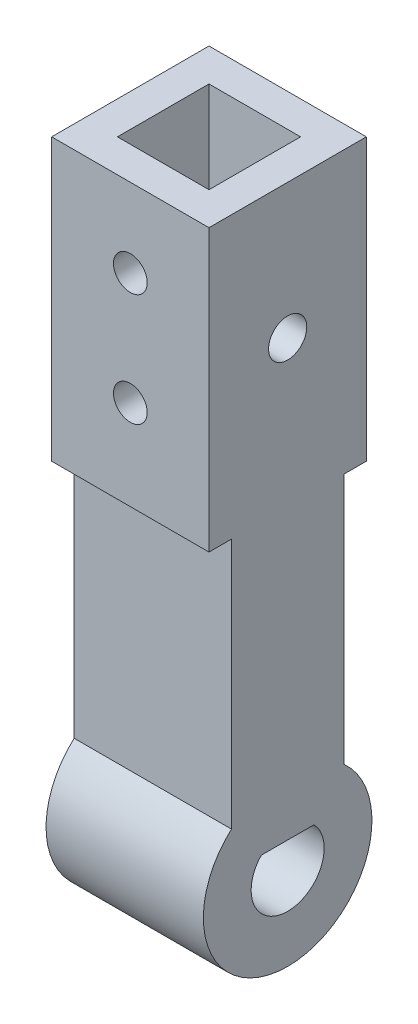
SolidWorks part; units mm, degrees
material "PLA"
ref_plane "Plan de face" through (0, 0, 0) normal (0, 0, 1) x (1, 0, 0)
ref_plane "Plan de dessus" through (0, 0, 0) normal (0, 1, 0) x (1, 0, 0)
ref_plane "Plan de droite" through (0, 0, 0) normal (1, 0, 0) x (0, 0, -1)
sketch "Esquisse1" plane through (0, 0, 0) normal (0, 0, 1) x (1, 0, 0)
  line L1 (0, 0) -> (140, 0) construction
  line L2 (0, 0) -> (0, 155) construction
  line L3 (0, 155) -> (140, 155) construction
  line L4 (140, 0) -> (140, 155) construction
  line L16 (65, 0) -> (65, 121.945)
  line L17 (65, 121.945) -> (0, 145.6031)
  line L18 (0, 145.6031) -> (3.4202, 155)
  line L19 (3.4202, 155) -> (70, 130.7669)
  line L20 (70, 130.7669) -> (136.5798, 155)
  line L21 (136.5798, 155) -> (140, 145.6031)
  line L22 (140, 145.6031) -> (75, 121.945)
  line L23 (75, 121.945) -> (75, 0)
  line L24 (75, 0) -> (65, 0)
  point P19 (70, 0)
  dimension "D1" = 140
  dimension "D2" = 155
  dimension "D3" = 10
  dimension "D4" = 70
  dimension "D5" = 110
  dimension "D6" = 110
  dimension "D7" = 140
  dimension "D8" = 10
  dimension "D9" = 10
  dimension "D10" = 70
extrude "Boss.-Extru.1" add sketch "Esquisse1" along normal blind 10
sketch "Esquisse2" plane through (0, 0, 0) normal (0, 0, -1) x (-1, 0, 0)
  line L0 (-75, 121.945) -> (-140, 145.6031) construction
  line L1 (-140, 145.6031) -> (-136.5798, 155) construction
  line L2 (-136.5798, 155) -> (-70, 130.7669) construction
  line L3 (-135.3015, 143.893) -> (-140, 145.6031)
  line L4 (-140, 145.6031) -> (-136.5798, 155)
  line L5 (-136.5798, 155) -> (-127.1829, 151.5798)
  line L6 (-128.893, 146.8813) -> (-127.1829, 151.5798)
  line L7 (0, 145.6031) -> (-65, 121.945) construction
  line L8 (-70, 130.7669) -> (-3.4202, 155) construction
  line L9 (-3.4202, 155) -> (0, 145.6031) construction
  line L10 (0, 145.6031) -> (-4.6985, 143.893)
  line L11 (-12.8171, 151.5798) -> (-3.4202, 155)
  line L12 (-3.4202, 155) -> (0, 145.6031)
  line L13 (-12.8171, 151.5798) -> (-11.107, 146.8813)
  line L14 (-135.3015, 143.893) -> (-128.893, 146.8813)
  line L15 (-11.107, 146.8813) -> (-4.6985, 143.893)
  dimension "D1" = 10
  dimension "D2" = 10
  dimension "D3" = 5
  dimension "D4" = 5
  dimension "D5" = 5
  dimension "D6" = 5
extrude "Boss.-Extru.2" add sketch "Esquisse2" along normal blind 15
fillet "Congé1" radius 20 3 edges at (75, 121.945, 5) (65, 121.945, 5) (70, 130.7669, 5)
fillet "Congé2" radius 4 2 edges at (138.2899, 150.3015, 10) (1.7101, 150.3015, 10)
sketch "Esquisse3" plane through (65, 0, 0) normal (-1, 0, 0) x (0, 0, 1)
  line L0 (5, 0) -> (5, 33.6289) construction
  line L1 (10, 0) -> (0, 0) construction
  circle A0 centre (5, 0) radius 7.5
  dimension "D1" = 15
extrude "Boss.-Extru.3" add sketch "Esquisse3" against normal up to surface (10 mm away) up to face at (75, 53.9704, 5)
sketch "Esquisse7" plane through (0, 0, 10) normal (0, 0, 1) x (1, 0, 0)
  line L0 (3.4202, 155) -> (0, 145.6031)
  line L1 (0, 145.6031) -> (51.8404, 126.7347)
  line L2 (65, 107.9409) -> (65, 27.9409)
  line L3 (65, 107.9409) -> (65, 5.5902) construction
  line L4 (65, 27.9409) -> (75, 27.9409)
  line L5 (75, 5.5902) -> (75, 107.9409) construction
  line L6 (75, 27.9409) -> (75, 107.9409)
  line L7 (88.1596, 126.7347) -> (140, 145.6031)
  line L8 (140, 145.6031) -> (136.5798, 155)
  line L9 (136.5798, 155) -> (76.8404, 133.2566)
  line L10 (63.1596, 133.2566) -> (3.4202, 155)
  arc A0 (51.8404, 126.7347) -> (65, 107.9409) centre (45, 107.9409) cw
  arc A1 (75, 107.9409) -> (88.1596, 126.7347) centre (95, 107.9409) cw
  arc A2 (76.8404, 133.2566) -> (63.1596, 133.2566) centre (70, 152.0505) cw
  dimension "D1" = 80
extrude "Enlèv. mat.-Extru.1" cut sketch "Esquisse7" against normal up to surface (25 mm away) up to face at (133.5914, 148.5914, -15)
sketch "Esquisse11" plane through (0, 27.9409, 0) normal (0, 1, 0) x (1, 0, 0)
  line L0 (65, 0) -> (65, -10) construction
  line L1 (61, 2) -> (75, 2)
  line L2 (61, 2) -> (61, -12)
  line L3 (61, -12) -> (75, -12)
  line L4 (75, 2) -> (75, -12)
  line L5 (65, -10) -> (75, -10) construction
  dimension "D1" = 14
  dimension "D2" = 14
  dimension "D3" = 4
  dimension "D4" = 2
extrude "Boss.-Extru.4" add sketch "Esquisse11" along normal blind 25
sketch "Esquisse12" plane through (0, 52.9409, 0) normal (0, 1, 0) x (1, 0, 0)
  line L0 (68, 2) -> (68, -12) construction
  line L1 (63.925, -0.925) -> (72.075, -0.925)
  line L2 (63.925, -0.925) -> (63.925, -9.075)
  line L3 (63.925, -9.075) -> (72.075, -9.075)
  line L4 (72.075, -0.925) -> (72.075, -9.075)
  line L5 (75, 2) -> (61, 2) construction
  line L6 (61, -12) -> (75, -12) construction
  line L7 (61, -5) -> (75, -5) construction
  line L8 (61, 2) -> (61, -12) construction
  line L9 (75, -12) -> (75, 2) construction
  line L10 (68, -0.925) -> (68, -9.075) construction
  line L11 (63.925, -5) -> (72.075, -5) construction
  dimension "D1" = 8.15
  dimension "D2" = 8.15
extrude "Enlèv. mat.-Extru.4" cut sketch "Esquisse12" against normal blind 20
sketch "Esquisse13" plane through (61, 0, 0) normal (-1, 0, 0) x (0, 0, 1)
  line L2 (12, 52.9409) -> (12, 27.9409) construction
  line L3 (-2, 52.9409) -> (12, 52.9409) construction
  circle A0 centre (5, 40.9409) radius 1.5
  point P6 (-20.9791, 50.3627)
  point P7 (11, 42.4778)
  dimension "D3" = 3
  dimension "D1" = 12
  dimension "D2" = 7
extrude "Enlèv. mat.-Extru.5" cut sketch "Esquisse13" against normal up to surface (14 mm away) up to face at (75, 26.9669, 5)
sketch "Esquisse4" plane through (65, 0, 0) normal (-1, 0, 0) x (0, 0, 1)
  line L7 (5, 0) -> (5, 7.4852) construction
  line L11 (2.6548, 2.25) -> (7.3452, 2.25)
  line L12 (0.3981, -3.25) -> (8.2082, -3.25) construction
  arc A1 (2.6548, 2.25) -> (7.3452, 2.25) centre (5, 0) ccw
  point P10 (5, 6)
  point P11 (5, 6)
  dimension "D1" = 6.5
  dimension "D2" = 5.5
extrude "Enlèv. mat.-Extru.2" cut sketch "Esquisse4" against normal blind 20
sketch "Esquisse15" plane through (0, 0, 12) normal (0, 0, 1) x (1, 0, 0)
  line L0 (75, 52.9409) -> (75, 27.9409) construction
  line L1 (61, 52.9409) -> (75, 52.9409) construction
  line L2 (61, 27.9409) -> (75, 27.9409) construction
  circle A1 centre (68, 45.9409) radius 1.5
  circle A2 centre (68, 35.9409) radius 1.5
  dimension "D5" = 3
  dimension "D6" = 3
  dimension "D1" = 7
  dimension "D2" = 7
  dimension "D3" = 7
  dimension "D4" = 8
extrude "Enlèv. mat.-Extru.6" cut sketch "Esquisse15" against normal up to surface (14 mm away) up to face at (68, 40.4409, -2)
hole_wizard "Dégagement M31" positions "Esquisse16" profile "Esquisse17" hole size "M3" standard "ISO"
sketch "Esquisse16" plane through (0, 0, -2) normal (0, 0, -1) x (-1, 0, 0)
  point P0 (-68, 45.9409)
  point P3 (-68, 35.9409)
sketch "Esquisse17" plane through (68, 45.9409, -2) normal (1, 0, 0) x (0, 1, 0)
  line L0 (0, 0) -> (0, 11.0215)
  line L1 (0, 11.0215) -> (1.7, 10)
  line L2 (1.7, 10) -> (1.7, 0)
  line L5 (1.7, 0) -> (0, 0)
  line L10 (0, 11.0215) -> (-1.7, 10) construction
  line L11 (0, -6.35) -> (0, 107.95) construction
  dimension "Diamètre du perçage" = 3.4
  dimension "Profondeur du perçage" = 10
  dimension "Angle de pointe" = 118
hole_wizard "Dégagement M32" positions "Esquisse18" profile "Esquisse19" hole size "M3" standard "ISO"
sketch "Esquisse18" plane through (75, 0, 0) normal (1, 0, 0) x (0, 0, -1)
  point P0 (-5, 40.9409)
sketch "Esquisse19" plane through (75, 40.9409, 5) normal (0, 1, 0) x (0, 0, -1)
  line L0 (0, 0) -> (0, 11.0215)
  line L1 (0, 11.0215) -> (1.7, 10)
  line L2 (1.7, 10) -> (1.7, 0)
  line L5 (1.7, 0) -> (0, 0)
  line L10 (0, 11.0215) -> (-1.7, 10) construction
  line L11 (0, -6.35) -> (0, 107.95) construction
  dimension "Diamètre du perçage" = 3.4
  dimension "Profondeur du perçage" = 10
  dimension "Angle de pointe" = 118
sketch "Esquisse20" plane through (65, 0, 0) normal (-1, 0, 0) x (0, 0, 1)
  line L0 (10, 5.5902) -> (10, 27.9409)
  line L1 (-2, 27.9409) -> (12, 27.9409) construction
  line L2 (10, 27.9409) -> (10, 5.5902) construction
  line L3 (10, 27.9409) -> (0, 27.9409)
  line L4 (0, 27.9409) -> (0, 5.5902)
  line L5 (7.3452, 2.25) -> (2.6548, 2.25)
  arc A0 (0, 5.5902) -> (10, 5.5902) centre (5, 0) ccw
  arc A1 (2.6548, 2.25) -> (7.3452, 2.25) centre (5, 0) ccw
extrude "Boss.-Extru.6" add sketch "Esquisse20" along normal blind 4
equation "\"long_tot\"=155"
equation "\"espac_sub_arms\"= 120"
equation "\"épaiss_cadre\"=10"
equation "\"long_protub\"= 15"
equation "\"rayon_conge\"= 3"
equation "\"diam_axe\"= 5"
equation "\"D1@Esquisse1\"=\"espac_sub_arms\"+\"épaiss_cadre\"*2"
equation "\"D2@Esquisse1\"=\"long_tot\""
equation "\"D3@Esquisse1\"=\"épaiss_cadre\""
equation "\"D4@Esquisse1\"=\"D1@Esquisse1\"/2"
equation "\"D6@Esquisse1\"=\"D5@Esquisse1\""
equation "\"D8@Esquisse1\"=\"épaiss_cadre\""
equation "\"D9@Esquisse1\"=\"épaiss_cadre\""
equation "\"D10@Esquisse1\"=\"D4@Esquisse1\""
equation "\"D1@Boss.-Extru.1\"=\"épaiss_cadre\""
equation "\"D2@Esquisse2\"=\"épaiss_cadre\""
equation "\"D1@Boss.-Extru.2\"=\"long_protub\""
equation "\"D1@Esquisse2\"=\"épaiss_cadre\""
equation "\"D3@Esquisse2\"=\"D1@Esquisse2\"/2"
equation "\"D4@Esquisse2\"=\"D1@Esquisse2\"/2"
equation "\"D5@Esquisse2\"=\"D2@Esquisse2\"/2"
equation "\"D6@Esquisse2\"=\"D2@Esquisse2\"/2"
